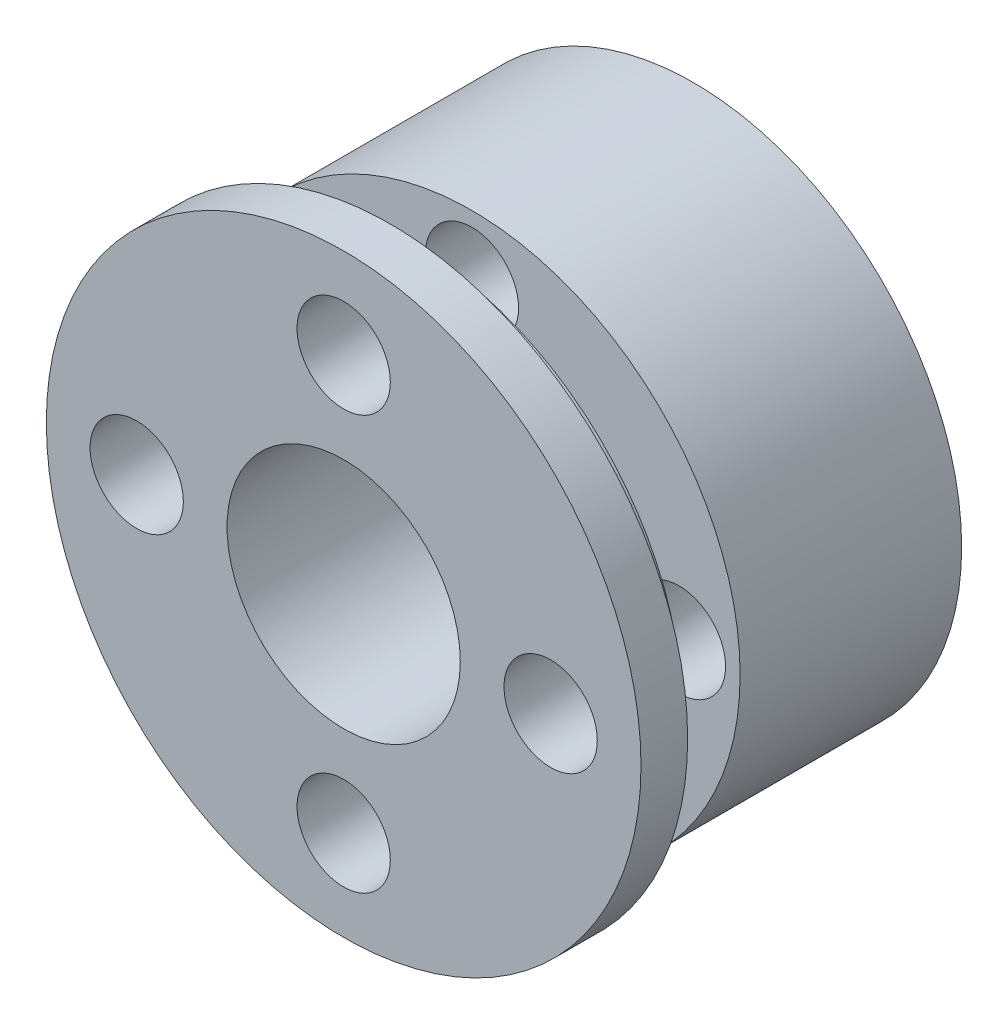
SolidWorks part; units mm, degrees
ref_plane "Front Plane" through (0, 0, 0) normal (0, 0, 1) x (1, 0, 0)
ref_plane "Top Plane" through (0, 0, 0) normal (0, 1, 0) x (1, 0, 0)
ref_plane "Right Plane" through (0, 0, 0) normal (1, 0, 0) x (0, 0, -1)
sketch "Sketch1" plane through (0, 0, 0) normal (1, 0, 0) x (0, 0, -1)
  line L0 (0, 0) -> (0, 11.5)
  line L1 (0, 11.5) -> (-9.5, 11.5)
  line L2 (-9.5, 11.5) -> (-9.5, 6)
  line L3 (-9.5, 6) -> (-12, 6)
  line L4 (-12, 6) -> (-12, 11.5)
  line L5 (-12, 11.5) -> (-13, 11.5)
  line L6 (-13, 11.5) -> (-13, 12.75)
  line L7 (-13, 12.75) -> (-15, 12.75)
  line L8 (-15, 12.75) -> (-15, 0)
  line L12 (-15, 0) -> (0, 0)
  dimension "D1" = 11.5
  dimension "D2" = 9.5
  dimension "D3" = 13
  dimension "D4" = 15
  dimension "D5" = 12.75
  dimension "D6" = 6
revolve "Revolve1" add sketch "Sketch1" angle 360 about L12
sketch "Sketch2" plane through (0, 0, 15) normal (0, 0, 1) x (1, 0, 0)
  circle A0 centre (0, 0) radius 5
  dimension "D1" = 10
extrude "Cut-Extrude1" cut sketch "Sketch2" against normal through all
sketch "Sketch3" plane through (0, 0, 15) normal (0, 0, 1) x (1, 0, 0)
  circle A0 centre (0, 8.875) radius 2
  circle A1 centre (8.875, 0) radius 2
  circle A2 centre (0, -8.875) radius 2
  circle A3 centre (-8.875, 0) radius 2
  point P12 (0, 0)
  dimension "D1" = 4
  dimension "D2" = 8.875
  dimension "D3" = 4
extrude "Cut-Extrude2" cut sketch "Sketch3" against normal through all contours A0
